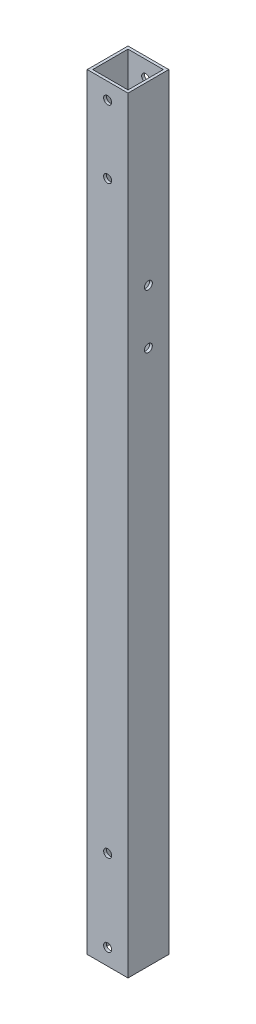
SolidWorks part; units mm, degrees
ref_plane "前视基准面" through (0, 0, 0) normal (0, 0, 1) x (1, 0, 0)
ref_plane "上视基准面" through (0, 0, 0) normal (0, 1, 0) x (1, 0, 0)
ref_plane "右视基准面" through (0, 0, 0) normal (1, 0, 0) x (0, 0, -1)
sketch "草图1" plane through (0, 0, 0) normal (0, 1, 0) x (1, 0, 0)
  line L1 (-7.5, -7.5) -> (7.5, -7.5)
  line L2 (-7.5, -7.5) -> (-7.5, 7.5)
  line L3 (-7.5, 7.5) -> (7.5, 7.5)
  line L4 (7.5, -7.5) -> (7.5, 7.5)
  line L5 (-7.5, -7.5) -> (7.5, 7.5) construction
  line L6 (-7.5, 7.5) -> (7.5, -7.5) construction
  point P0 (0, 0)
  dimension "D1" = 15
  dimension "D2" = 15
extrude "拉伸-薄壁1" add sketch "草图1" along normal blind 282 thin thin type one direction reverse wall 1
sketch "草图2" plane through (0, 0, 7.5) normal (0, 0, 1) x (1, 0, 0)
  line L0 (0, 0) -> (0, 282) construction
  line L1 (-7.5, 282) -> (7.5, 282) construction
  line L2 (-7.5, 0) -> (7.5, 0) construction
  circle A0 centre (0, 36) radius 1.475
  circle A1 centre (0, 6) radius 1.475
  circle A2 centre (0, 276) radius 1.475
  circle A3 centre (0, 251) radius 1.475
  dimension "D1" = 2.95
  dimension "D2" = 30
  dimension "D3" = 25
  dimension "D4" = 215
  dimension "D5" = 6
extrude "切除-拉伸1" cut sketch "草图2" against normal through all
sketch "草图3" plane through (7.5, 0, 0) normal (1, 0, 0) x (0, 0, -1)
  line L0 (0, 0) -> (0, 282) construction
  line L1 (-7.5, 282) -> (7.5, 282) construction
  circle A0 centre (0, 217) radius 1.45
  circle A1 centre (0, 197) radius 1.45
  dimension "D1" = 2.9
  dimension "D2" = 65
  dimension "D3" = 20
extrude "切除-拉伸2" cut sketch "草图3" against normal through all
